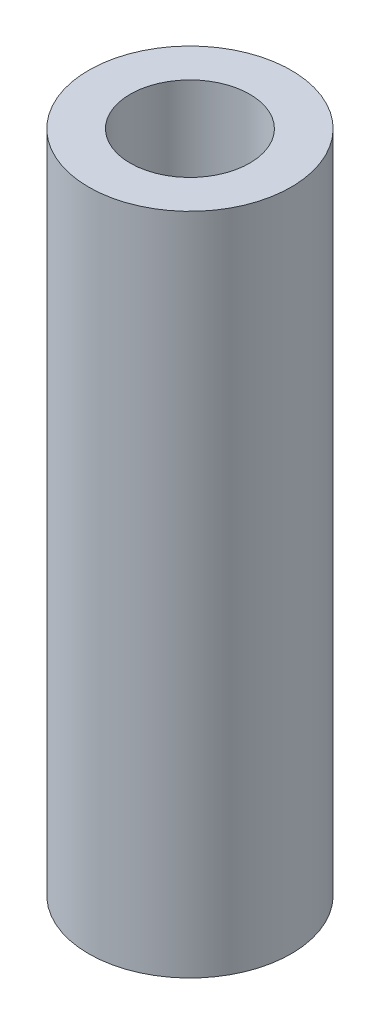
SolidWorks part; units mm, degrees
ref_plane "Alzado" through (0, 0, 0) normal (0, 0, 1) x (1, 0, 0)
ref_plane "Planta" through (0, 0, 0) normal (0, 1, 0) x (1, 0, 0)
ref_plane "Vista lateral" through (0, 0, 0) normal (1, 0, 0) x (0, 0, -1)
sketch "Croquis base" plane through (0, 0, 0) normal (0, 1, 0) x (1, 0, 0)
  circle A0 centre (0, 0) radius 1.525
  circle A1 centre (0, 0) radius 0.9
extrude "Saliente-Extruir1" add sketch "Croquis base" along normal blind 10
